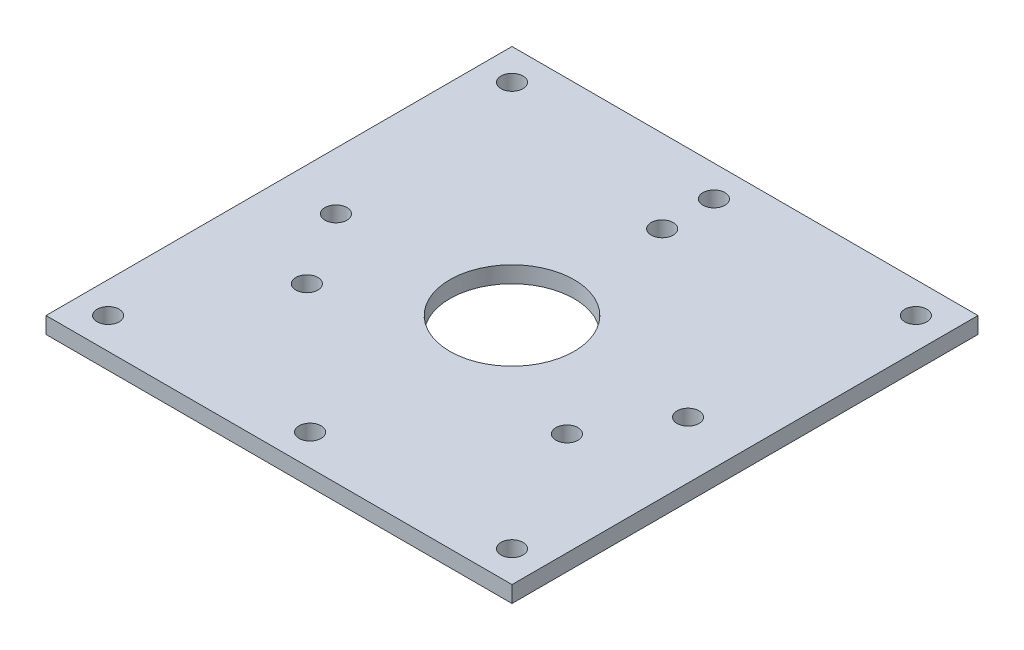
SolidWorks part; units mm, degrees
ref_plane "Front Plane" through (0, 0, 0) normal (0, 0, 1) x (1, 0, 0)
ref_plane "Top Plane" through (0, 0, 0) normal (0, 1, 0) x (1, 0, 0)
ref_plane "Right Plane" through (0, 0, 0) normal (1, 0, 0) x (0, 0, -1)
sketch "Sketch1" plane through (0, 0, 0) normal (0, 1, 0) x (1, 0, 0)
  line L0 (-45, 0) -> (45, 0) construction
  line L1 (-45, -45) -> (45, -45)
  line L2 (-45, -45) -> (-45, 45)
  line L3 (-45, 45) -> (45, 45)
  line L4 (45, -45) -> (45, 45)
  line L5 (-45, -45) -> (45, 45) construction
  line L6 (-45, 45) -> (45, -45) construction
  line L7 (0, 45) -> (0, -45) construction
  circle A0 centre (0, 0) radius 12
  circle A1 centre (0, 29) radius 2.125
  circle A2 centre (25.1147, -14.5) radius 2.125
  circle A3 centre (-25.1147, -14.5) radius 2.125
  circle A4 centre (-39, -39) radius 2.125
  circle A5 centre (-34, 0) radius 2.125
  circle A6 centre (-39, 39) radius 2.125
  circle A7 centre (39, -39) radius 2.125
  circle A8 centre (34, 0) radius 2.125
  circle A9 centre (39, 39) radius 2.125
  circle A10 centre (0, -39) radius 2.125
  circle A11 centre (0, 39) radius 2.125
  point P0 (0, 0)
  point P16 (0, 0)
  point P33 (0, -44)
  point P34 (0, -39)
  dimension "D1" = 24
  dimension "D2" = 4.25
  dimension "D7" = 4.25
  dimension "D10" = 4.25
  dimension "D11" = 4.25
  dimension "D3" = 29
  dimension "D5" = 90
  dimension "D6" = 90
  dimension "D8" = 6
  dimension "D9" = 6
  dimension "D12" = 6
  dimension "D4" = 3
extrude "Boss-Extrude1" add sketch "Sketch1" along normal blind 3.175
